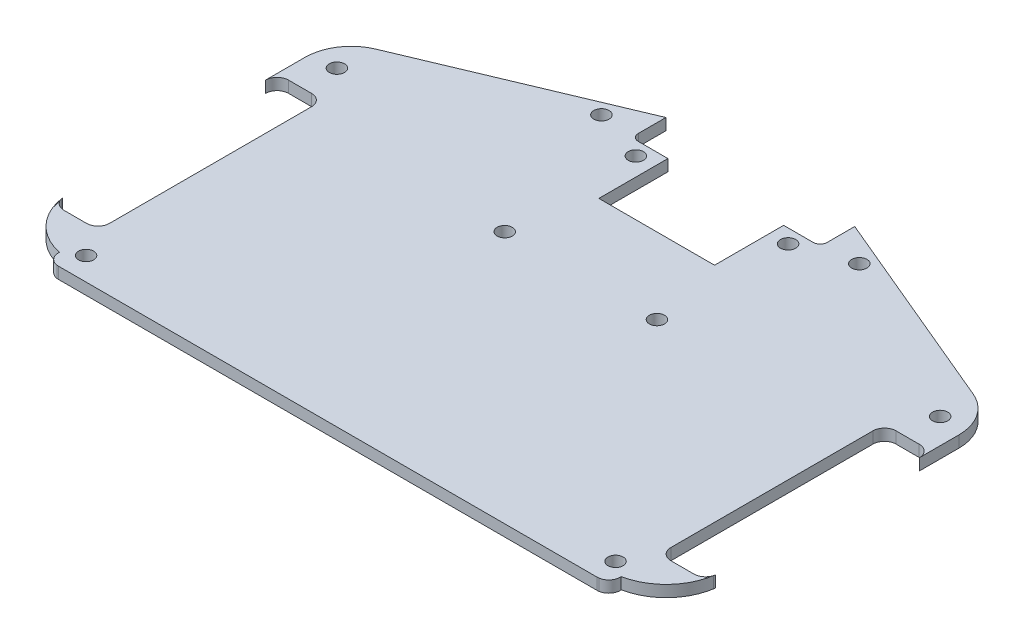
SolidWorks part; units mm, degrees
ref_plane "Front Plane" through (0, 0, 0) normal (0, 0, 1) x (1, 0, 0)
ref_plane "Top Plane" through (0, 0, 0) normal (0, 1, 0) x (1, 0, 0)
ref_plane "Right Plane" through (0, 0, 0) normal (1, 0, 0) x (0, 0, -1)
sketch "Sketch2" plane through (0, 0, 0) normal (0, 1, 0) x (1, 0, 0)
  line L0 (41, 93.9081) -> (129.7473, 56.6193)
  line L1 (142, 21.0252) -> (142, 38.1808)
  line L2 (126.8106, 26.0252) -> (136.8106, 26.0216)
  line L3 (121.8106, 21.0252) -> (121.8106, -66.7248)
  line L4 (-25.12, 78.9081) -> (-25.12, 48.9081)
  line L5 (25.12, 78.9081) -> (25.12, 48.9081)
  line L6 (126.8106, -71.7248) -> (136.8106, -71.7248)
  line L7 (-117, -93.9121) -> (117, -93.9121)
  line L8 (-136.8106, -71.7248) -> (-127, -71.7248)
  line L9 (-122, 21.0252) -> (-122, -66.7248)
  line L10 (25.12, 48.9081) -> (-25.12, 48.9081)
  line L12 (-137, 26.0252) -> (-127, 26.0252)
  line L13 (-142, 38.1808) -> (-142, 21.0252)
  line L14 (-41, 93.9081) -> (-129.7473, 56.6193)
  line L15 (-38, 78.9081) -> (-25.12, 78.9081)
  line L18 (38, 78.9081) -> (25.12, 78.9081)
  line L20 (-41, 93.9081) -> (-41, 81.9081)
  line L22 (41, 93.9081) -> (41, 81.9081)
  arc A0 (142, 38.1808) -> (129.7473, 56.6193) centre (122, 38.1808) ccw
  arc A1 (142, 21.0252) -> (136.8106, 26.0216) centre (137, 21.0252) ccw
  arc A2 (126.8106, 26.0252) -> (121.8106, 21.0252) centre (126.8106, 21.0252) ccw
  arc A3 (121.8106, -66.7248) -> (126.8106, -71.7248) centre (126.8106, -66.7248) ccw
  arc A4 (136.8106, -71.7248) -> (141.7632, -67.4113) centre (136.8106, -66.7248) ccw
  arc A5 (121.9811, -88.4776) -> (141.7632, -67.4113) centre (117, -63.9788) ccw
  arc A6 (117.797, -93.8482) -> (121.9811, -88.4776) centre (117, -88.9121) ccw
  arc A7 (-117.797, -93.8482) -> (-117, -93.9121) centre (-115, -63.9788) ccw
  arc A8 (-121.9811, -88.4776) -> (-117.797, -93.8482) centre (-117, -88.9121) ccw
  arc A9 (-141.7632, -67.4113) -> (-121.9811, -88.4776) centre (-117, -63.9788) ccw
  arc A10 (117, -93.9121) -> (117.797, -93.8482) centre (115, -63.9788) ccw
  arc A11 (-141.7632, -67.4113) -> (-136.8106, -71.7248) centre (-136.8106, -66.7248) ccw
  arc A12 (-127, -71.7248) -> (-122, -66.7248) centre (-127, -66.7248) ccw
  arc A13 (-122, 21.0252) -> (-127, 26.0252) centre (-127, 21.0252) ccw
  arc A14 (-137, 26.0252) -> (-142, 21.0252) centre (-137, 21.0252) ccw
  arc A15 (-129.7473, 56.6193) -> (-142, 38.1808) centre (-122, 38.1808) ccw
  arc A16 (-41, 81.9081) -> (-38, 78.9081) centre (-38, 81.9081) ccw
  arc A19 (38, 78.9081) -> (41, 81.9081) centre (38, 81.9081) ccw
  circle A20 centre (-33.06, 15.9548) radius 3.3
  circle A21 centre (33.06, 15.9548) radius 3.3
  circle A22 centre (33.06, 72.9081) radius 3.3
  circle A23 centre (-33.06, 72.9081) radius 3.3
  circle A24 centre (-56, 80.9081) radius 3.3
  circle A25 centre (-131, 41.0252) radius 3.3
  circle A26 centre (56, 80.9081) radius 3.3
  circle A27 centre (131, 41.0252) radius 3.3
  circle A28 centre (115, -83.9748) radius 3.3
  circle A29 centre (-115, -83.9081) radius 3.3
  dimension "D1" = 6.6
  dimension "D7" = 6.6
  dimension "D8" = 6.6
  dimension "D9" = 6.6
  dimension "D10" = 6.6
  dimension "D11" = 6.6
  dimension "D12" = 6.6
  dimension "D13" = 6.6
  dimension "D14" = 6.6
  dimension "D15" = 6.6
  dimension "D16" = 5
  dimension "D17" = 5
  dimension "D18" = 25
  dimension "D19" = 25
  dimension "D24" = 3
  dimension "D25" = 3
  dimension "D26" = 5
  dimension "D27" = 5
  dimension "D29" = 5
  dimension "D30" = 5
  dimension "D34" = 5
  dimension "D35" = 5
  dimension "D37" = 20
  dimension "D38" = 5
  dimension "D39" = 5
  dimension "D2" = 87.75
  dimension "D3" = 87.75
  dimension "D4" = 234
  dimension "D5" = 88.7473
  dimension "D6" = 88.7473
  dimension "D20" = 12
  dimension "D21" = 12
  dimension "D22" = 12.88
  dimension "D23" = 12.88
  dimension "D28" = 10
  dimension "D31" = 10
  dimension "D32" = 9.8106
  dimension "D33" = 10
  dimension "D36" = 17.1556
  dimension "D40" = 17.1556
  dimension "D41" = 30
  dimension "D42" = 50.24
  dimension "D43" = 30
  dimension "D44" = 56.9533
  dimension "D45" = 56.9533
  dimension "D46" = 6
extrude "Ressalto-extrusão3" add sketch "Sketch2" along normal mid plane 5
